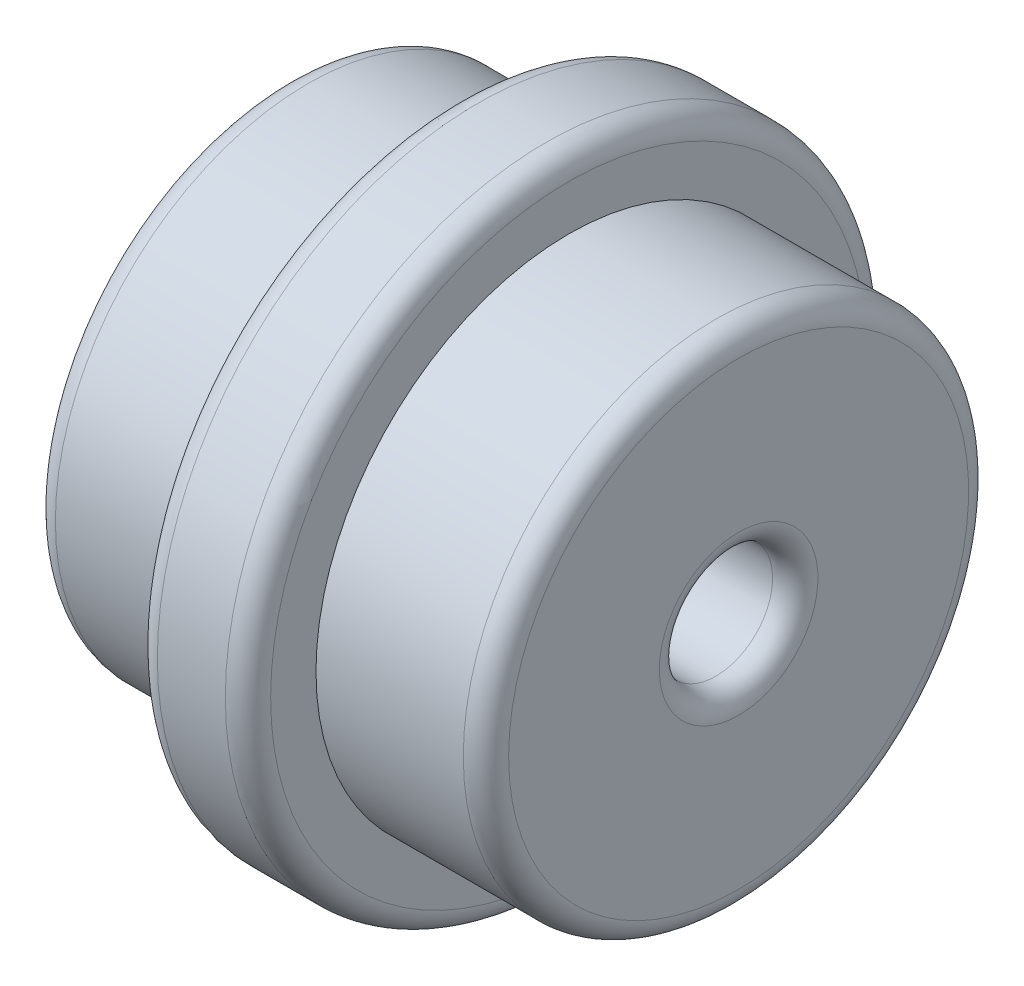
SolidWorks part; units mm, degrees
material "ABS"
ref_plane "Plan de face" through (0, 0, 0) normal (0, 0, 1) x (1, 0, 0)
ref_plane "Plan de dessus" through (0, 0, 0) normal (0, 1, 0) x (1, 0, 0)
ref_plane "Plan de droite" through (0, 0, 0) normal (1, 0, 0) x (0, 0, -1)
sketch "Esquisse1" plane through (0, 0, 0) normal (0, 0, 1) x (1, 0, 0)
  line L0 (-10, 0) -> (10, 0)
  line L1 (10, 0) -> (10, 11.15)
  line L2 (10, 11.15) -> (2.5, 11.15)
  line L3 (2.5, 11.15) -> (2.5, 14.15)
  line L4 (2.5, 14.15) -> (-2.5, 14.15)
  line L5 (-2.5, 14.15) -> (-2.5, 11.15)
  line L6 (-2.5, 11.15) -> (-10, 11.15)
  line L7 (-10, 11.15) -> (-10, 0)
  dimension "D1" = 20
  dimension "D2" = 10
  dimension "D3" = 11.15
  dimension "D4" = 14.15
  dimension "D5" = 7.5
  dimension "D6" = 12.5
revolve "Révolution1" add sketch "Esquisse1" angle 360 about L0
fillet "Congé1" radius 1 4 edges at (-10, 0, 11.15) (10, 0, 11.15) (2.5, 0, 14.15) (-2.5, 0, 14.15)
sketch "Esquisse7" plane through (-10, 0, 0) normal (-1, 0, 0) x (0, 0, 1)
  circle A0 centre (0, 0) radius 2.5
  dimension "D1" = 5
extrude "Enlèv. mat.-Extru.3" cut sketch "Esquisse7" against normal blind 20
fillet "Congé2" radius 1 2 edges at (-10, 0, 2.5) (10, 0, 2.5)
